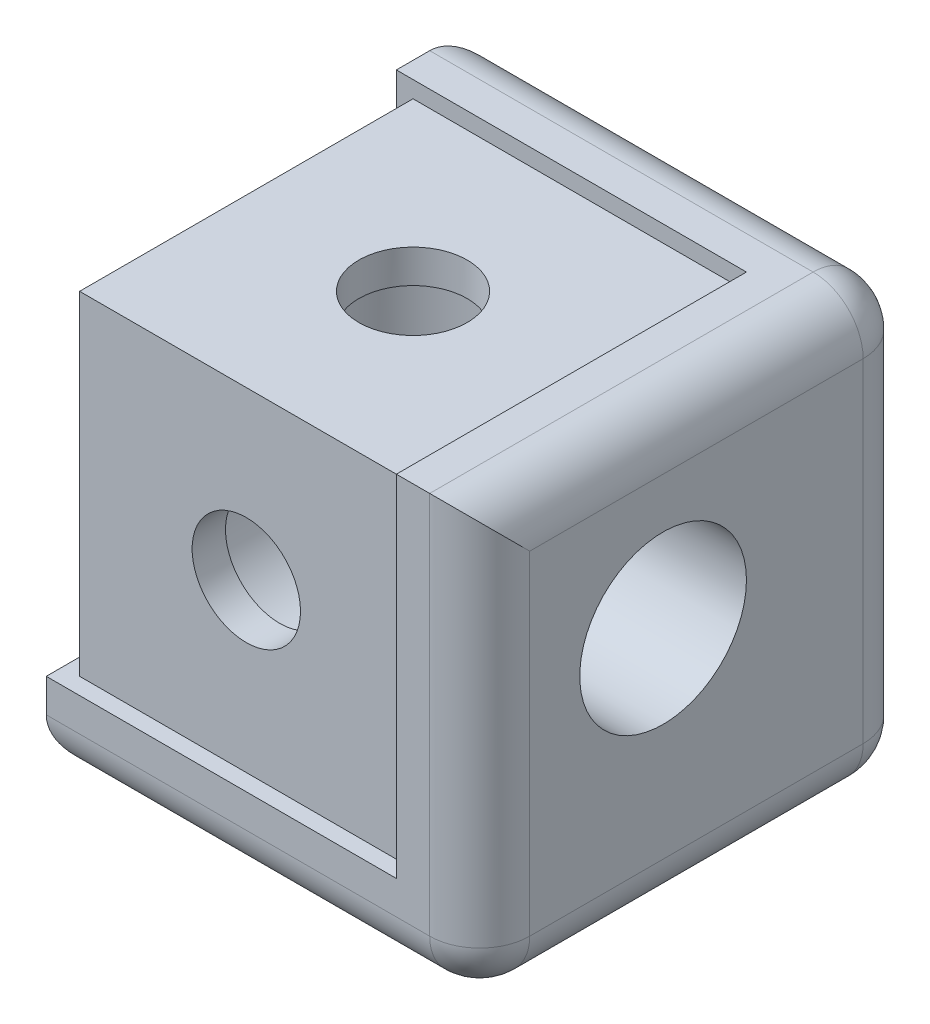
SolidWorks part; units mm, degrees
material "ABS"
ref_plane "Front Plane" through (0, 0, 0) normal (0, 0, 1) x (1, 0, 0)
ref_plane "Top Plane" through (0, 0, 0) normal (0, 1, 0) x (1, 0, 0)
ref_plane "Right Plane" through (0, 0, 0) normal (1, 0, 0) x (0, 0, -1)
sketch "Sketch2" plane through (0, 0, 0) normal (0, 1, 0) x (1, 0, 0)
  line L1 (0, 0) -> (25, 0)
  line L2 (0, 0) -> (0, 25)
  line L3 (0, 25) -> (25, 25)
  line L4 (25, 0) -> (25, 25)
  dimension "D1" = 25
  dimension "D2" = 25
extrude "Boss-Extrude1" add sketch "Sketch2" along normal blind 25
sketch "Sketch3" plane through (0, 25, 0) normal (0, 1, 0) x (1, 0, 0)
  line L0 (0, 0) -> (25, 0) construction
  line L1 (0, 25) -> (0, 0) construction
  circle A0 centre (10, 10) radius 3.25
  dimension "D1" = 6.5
  dimension "D2" = 10
  dimension "D3" = 10
extrude "Cut-Extrude1" cut sketch "Sketch3" against normal through all
sketch "Sketch4" plane through (0, 0, 0) normal (-1, 0, 0) x (0, 0, 1)
  line L0 (-25, 25) -> (0, 25) construction
  line L1 (0, 25) -> (0, 0) construction
  circle A0 centre (-10, 15) radius 3.25
  dimension "D1" = 6.5
  dimension "D2" = 10
  dimension "D3" = 10
extrude "Cut-Extrude2" cut sketch "Sketch4" against normal through all
sketch "Sketch5" plane through (0, 0, 0) normal (0, 0, 1) x (1, 0, 0)
  line L0 (0, 25) -> (0, 0) construction
  line L1 (0, 25) -> (25, 25) construction
  circle A0 centre (10, 15) radius 3.25
  dimension "D1" = 6.5
  dimension "D2" = 10
  dimension "D3" = 10
extrude "Cut-Extrude3" cut sketch "Sketch5" against normal through all
sketch "Sketch6" plane through (0, 0, -25) normal (0, 0, -1) x (-1, 0, 0)
  circle A0 centre (-10, 15) radius 5
  dimension "D1" = 10
extrude "Cut-Extrude4" cut sketch "Sketch6" against normal blind 23
sketch "Sketch7" plane through (25, 0, 0) normal (1, 0, 0) x (0, 0, -1)
  circle A0 centre (10, 15) radius 5
  dimension "D1" = 10
extrude "Cut-Extrude5" cut sketch "Sketch7" against normal blind 23
sketch "Sketch12" plane through (0, 0, 0) normal (0, -1, 0) x (1, 0, 0)
  circle A0 centre (10, -10) radius 5
  dimension "D1" = 10
extrude "Cut-Extrude9" cut sketch "Sketch12" against normal blind 23
sketch "Sketch19" plane through (0, 0, 0) normal (0, 0, 1) x (1, 0, 0)
  line L0 (20, 25) -> (20, 5)
  line L1 (0, 25) -> (25, 25) construction
  line L2 (20, 5) -> (0, 5)
  line L3 (0, 25) -> (0, 0) construction
  line L4 (0, 5) -> (0, 0)
  line L5 (0, 0) -> (25, 0)
  line L6 (25, 0) -> (25, 25)
  line L7 (25, 25) -> (20, 25)
  dimension "D1" = 20
  dimension "D2" = 20
extrude "Boss-Extrude2" add sketch "Sketch19" along normal blind 1
sketch "Sketch20" plane through (0, 25, 0) normal (0, 1, 0) x (1, 0, 0)
  line L0 (20, 0) -> (20, 20)
  line L1 (20, 20) -> (0, 20)
  line L2 (0, 25) -> (0, 0) construction
  line L3 (0, 20) -> (0, 25)
  line L4 (0, 25) -> (25, 25)
  line L5 (25, 25) -> (25, -1)
  line L6 (25, -1) -> (20, -1)
  line L7 (20, -1) -> (20, 0)
  dimension "D1" = 20
extrude "Boss-Extrude3" add sketch "Sketch20" along normal blind 1
sketch "Sketch21" plane through (0, 0, 0) normal (-1, 0, 0) x (0, 0, 1)
  line L1 (-20, 25) -> (-20, 5)
  line L2 (-20, 5) -> (0, 5)
  line L10 (-25, 0) -> (1, 0)
  line L11 (1, 0) -> (1, 5)
  line L12 (1, 5) -> (0, 5)
  line L13 (0, 5) -> (0, 25)
  line L14 (0, 25) -> (-20, 25)
  line L15 (-20, 25) -> (-20, 26)
  line L16 (-20, 26) -> (-25, 26)
  line L17 (-25, 26) -> (-25, 0)
  line L21 (0, 5) -> (0, 25)
  line L22 (0, 25) -> (-20, 25)
  line M3 (-25, 0) -> (1, 0)
  line M4 (1, 0) -> (1, 5)
  line M5 (1, 5) -> (0, 5)
  line M8 (-20, 25) -> (-20, 26)
  line M9 (-20, 26) -> (-25, 26)
  line M10 (-25, 26) -> (-25, 0)
  dimension "D1" = 0
extrude "Boss-Extrude4" add sketch "Sketch21" along normal blind 1 contours L2 L1 M8 M9 M10 M3 M4 M5
fillet "Fillet2" radius 3 9 edges at (12, 0, -25) (25, 0, -12) (25, 13, -25) (25, 13, 1) (12, 0, 1) (-1, 13, -25) (-1, 0, -12) (12, 26, -25) (25, 26, -12)
